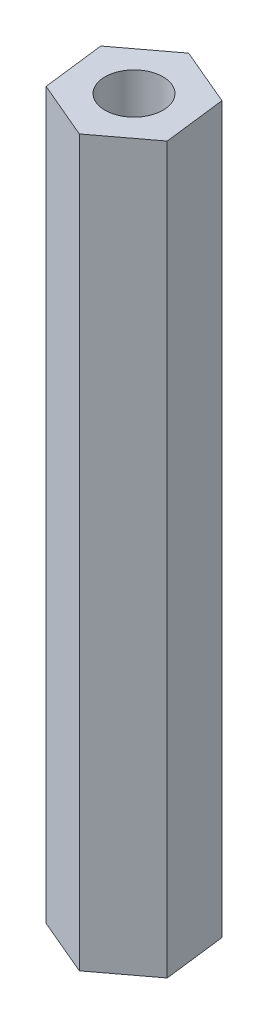
SolidWorks part; units mm, degrees
material "黄铜"
ref_plane "前视基准面" through (0, 0, 0) normal (0, 0, 1) x (1, 0, 0)
ref_plane "上视基准面" through (0, 0, 0) normal (0, 1, 0) x (1, 0, 0)
ref_plane "右视基准面" through (0, 0, 0) normal (1, 0, 0) x (0, 0, -1)
sketch "草图1" plane through (0, 0, 0) normal (0, 1, 0) x (1, 0, 0)
  line L1 (2.7672, 2.0839) -> (-0.4211, 3.4384)
  line L2 (-0.4211, 3.4384) -> (-3.1883, 1.3545)
  line L3 (-3.1883, 1.3545) -> (-2.7672, -2.0839)
  line L4 (-2.7672, -2.0839) -> (0.4211, -3.4384)
  line L5 (0.4211, -3.4384) -> (3.1883, -1.3545)
  line L6 (3.1883, -1.3545) -> (2.7672, 2.0839)
  circle A0 centre (0, 0) radius 1.6
  circle A1 centre (0, 0) radius 3 construction
  dimension "D1" = 3.2
extrude "凸台-拉伸1" add sketch "草图1" along normal blind 40
